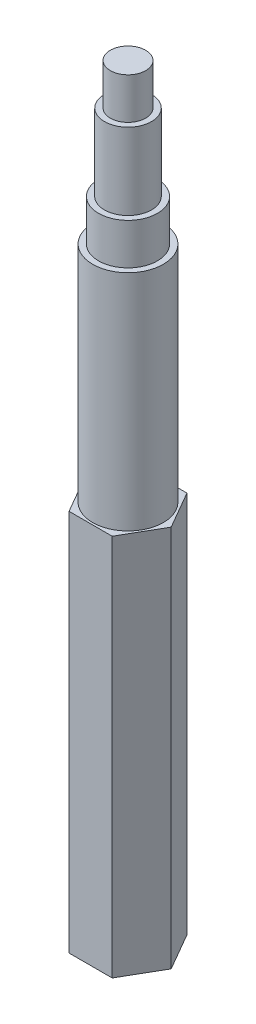
SolidWorks part; units mm, degrees
ref_plane "Alzado" through (0, 0, 0) normal (0, 0, 1) x (1, 0, 0)
ref_plane "Planta" through (0, 0, 0) normal (0, 1, 0) x (1, 0, 0)
ref_plane "Vista lateral" through (0, 0, 0) normal (1, 0, 0) x (0, 0, -1)
sketch "Croquis2" plane through (0, 0, 0) normal (0, 1, 0) x (1, 0, 0)
  line L0 (0, 0) -> (7.3323, 0) construction
  line L2 (7.3323, 0) -> (3.6662, 6.35)
  line L3 (3.6662, 6.35) -> (-3.6662, 6.35)
  line L4 (-3.6662, 6.35) -> (-7.3323, 0)
  line L5 (-7.3323, 0) -> (-3.6662, -6.35)
  line L6 (-3.6662, -6.35) -> (3.6662, -6.35)
  line L7 (3.6662, -6.35) -> (7.3323, 0)
  circle A0 centre (0, 0) radius 6.35 construction
  dimension "D1" = 12.7
extrude "Saliente-Extruir1" add sketch "Croquis2" along normal blind 130
sketch "Croquis3" plane through (0, 130, 0) normal (0, 1, 0) x (1, 0, 0)
  circle A0 centre (0, 0) radius 7.3323
  circle A1 centre (0, 0) radius 6
  dimension "D1" = 12
extrude "Cortar-Extruir1" cut sketch "Croquis3" against normal blind 65
sketch "Croquis4" plane through (0, 130, 0) normal (0, 1, 0) x (1, 0, 0)
  circle A0 centre (0, 0) radius 6
  circle A1 centre (0, 0) radius 5
  dimension "D1" = 12
  dimension "D2" = 10
extrude "Cortar-Extruir2" cut sketch "Croquis4" against normal blind 27
sketch "Croquis5" plane through (0, 130, 0) normal (0, 1, 0) x (1, 0, 0)
  circle A0 centre (0, 0) radius 5
  circle A1 centre (0, 0) radius 4
  dimension "D1" = 10
  dimension "D2" = 8
extrude "Cortar-Extruir3" cut sketch "Croquis5" against normal blind 20
sketch "Croquis6" plane through (0, 130, 0) normal (0, 1, 0) x (1, 0, 0)
  circle A0 centre (0, 0) radius 4
  circle A1 centre (0, 0) radius 4 construction
  circle A2 centre (0, 0) radius 3
  dimension "D1" = 6
extrude "Cortar-Extruir4" cut sketch "Croquis6" against normal blind 7
